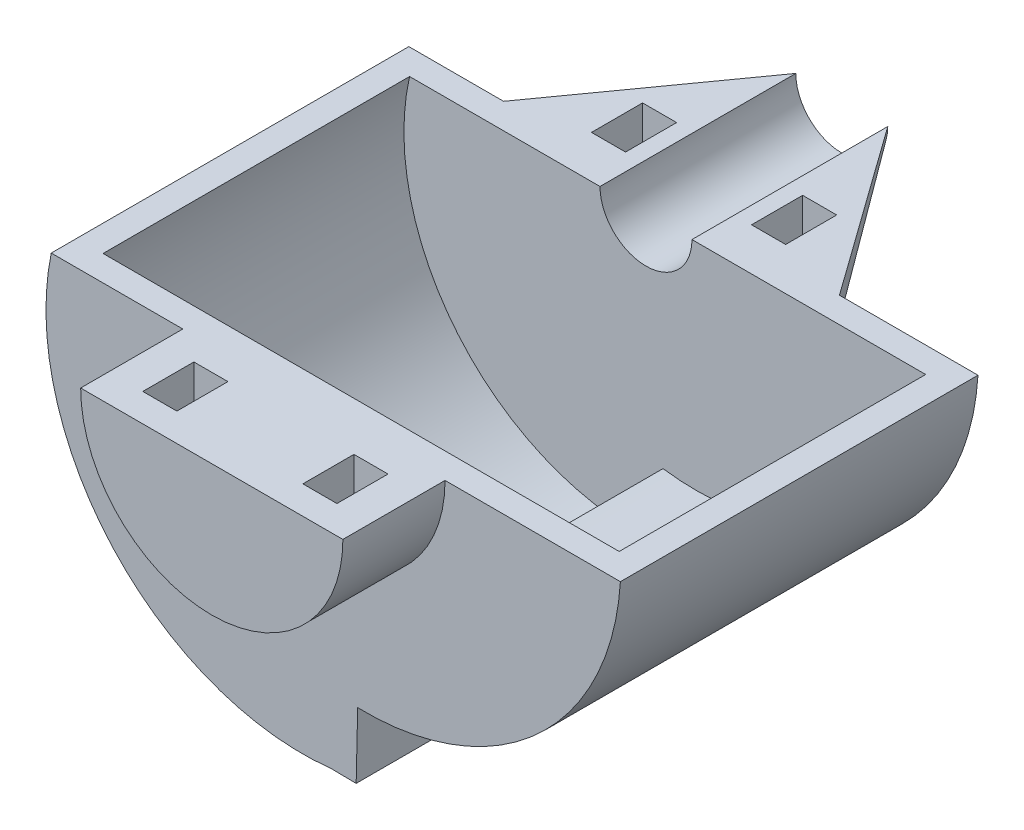
SolidWorks part; units mm, degrees
ref_plane "Alzado" through (0, 0, 0) normal (0, 0, 1) x (1, 0, 0)
ref_plane "Planta" through (0, 0, 0) normal (0, 1, 0) x (1, 0, 0)
ref_plane "Vista lateral" through (0, 0, 0) normal (1, 0, 0) x (0, 0, -1)
sketch "Croquis1" plane through (0, 0, 0) normal (0, 0, 1) x (1, 0, 0)
  line L0 (-54.5351, 31.4828) -> (-55.2579, 32.775)
  line L1 (-69.6242, 5.1176) -> (-68.6242, 5.1176)
  line L2 (-68.6242, 5.1176) -> (-68.6242, 9.1176)
  line L3 (-85.7122, 29.7526) -> (-86.47, 28.4805)
  line L4 (-83.9136, 29.8676) -> (-84.4136, 29.0016)
  line L5 (-84.4136, 29.0016) -> (-80.9495, 27.0016)
  line L6 (-86.47, 28.4805) -> (-83.1384, 26.453)
  line L7 (-55.3348, 29.8676) -> (-55.8348, 30.7337)
  line L8 (-55.8348, 30.7337) -> (-59.2989, 28.7337)
  line L9 (-55.2579, 32.775) -> (-58.6796, 30.9036)
  line L10 (-68.6253, 3.6175) -> (-67.1448, 3.5974)
  line L11 (-67.1448, 3.5974) -> (-67.0547, 7.4963)
  arc A1 (-69.6242, 5.1176) -> (-80.9495, 27.0016) centre (-70.3006, 18.6401) cw
  arc A2 (-55.3348, 29.8676) -> (-68.6242, 9.1176) centre (-66.7074, 22.5206) cw
  arc A3 (-83.9136, 29.8676) -> (-59.2989, 28.7337) centre (-71.8646, 23.6922) cw
  arc A4 (-83.1384, 26.453) -> (-68.6253, 3.6175) centre (-70.3045, 18.58) ccw
  arc A5 (-58.6796, 30.9036) -> (-85.7122, 29.7526) centre (-71.9148, 23.7256) ccw
  arc A6 (-67.0547, 7.4963) -> (-54.5351, 31.4828) centre (-66.6534, 22.5474) ccw
  point P16 (-69.6242, 21.6176)
  point P24 (-69.6242, 21.6176)
  point P33 (-69.6242, 21.6176)
  dimension "D1" = 3
  dimension "D2" = 3
  dimension "D5" = 3
extrude "Saliente-Extruir1" add sketch "Croquis1" along normal blind 18
sketch "Croquis2" plane through (0, 0, 0) normal (0, 0, -1) x (-1, 0, 0)
  line L0 (67.0547, 7.4963) -> (67.1448, 3.5974)
  line L1 (67.1448, 3.5974) -> (68.6253, 3.6175)
  line L2 (58.6796, 30.9036) -> (55.2579, 32.775)
  line L3 (55.2579, 32.775) -> (54.5351, 31.4828)
  line L4 (83.1384, 26.453) -> (86.47, 28.4805)
  line L5 (86.47, 28.4805) -> (85.7122, 29.7526)
  arc A0 (68.6253, 3.6175) -> (83.1384, 26.453) centre (70.3045, 18.58) ccw
  arc A2 (54.5351, 31.4828) -> (67.0547, 7.4963) centre (66.6534, 22.5474) ccw
  arc A3 (85.7122, 29.7526) -> (58.6796, 30.9036) centre (71.9148, 23.7256) ccw
  circle A4 centre (69.6242, 21.6176) radius 2.7
  point P26 (69.6242, 21.6176)
  dimension "D1" = 3
extrude "Saliente-Extruir2" add sketch "Croquis2" along normal blind 1.5
sketch "Croquis3" plane through (0, 0, 18) normal (0, 0, 1) x (1, 0, 0)
  line L0 (-67.1448, 3.5974) -> (-67.0547, 7.4963)
  line L2 (-67.1448, 3.5974) -> (-68.6253, 3.6175)
  line L3 (-86.47, 28.4805) -> (-83.1384, 26.453)
  line L4 (-86.47, 28.4805) -> (-85.7122, 29.7526)
  line L5 (-55.2579, 32.775) -> (-58.6796, 30.9036)
  line L6 (-55.2579, 32.775) -> (-54.5351, 31.4828)
  arc A0 (-68.6253, 3.6175) -> (-83.1384, 26.453) centre (-70.3045, 18.58) cw
  arc A2 (-85.7122, 29.7526) -> (-58.6796, 30.9036) centre (-71.9148, 23.7256) cw
  arc A3 (-54.5351, 31.4828) -> (-67.0547, 7.4963) centre (-66.6534, 22.5474) cw
  dimension "D1" = 3
extrude "Saliente-Extruir3" add sketch "Croquis3" along normal blind 1.5
sketch "Croquis6" plane through (0, 0, -1.5) normal (0, 0, -1) x (-1, 0, 0)
  line L1 (72.3242, 21.6176) -> (66.9242, 21.6176)
  line L2 (72.3242, 21.6176) -> (72.3242, 20.4357)
  line L3 (72.3242, 20.4357) -> (66.9242, 20.4357)
  line L4 (66.9242, 21.6176) -> (66.9242, 20.4357)
  circle A0 centre (69.6242, 21.6176) radius 2.7 construction
extrude "Saliente-Extruir7" add sketch "Croquis6" along normal blind 10
ref_plane "Plano2" through (0, 21.6176, 0) normal (0, 1, 0) x (1, 0, 0)
sketch "Croquis7" plane through (0, 21.6176, 0) normal (0, 1, 0) x (1, 0, 0)
  line L1 (-72.3242, 11.5) -> (-66.9242, 11.5)
  line L2 (-72.3242, 11.5) -> (-72.3242, 1.5)
  line L3 (-72.3242, 1.5) -> (-66.9242, 1.5)
  line L4 (-66.9242, 11.5) -> (-66.9242, 1.5)
extrude "Cortar-Extruir2" cut sketch "Croquis7" against normal up to vertex (16.5 mm away)
sketch "Croquis8" plane through (0, 21.6176, 0) normal (0, 1, 0) x (1, 0, 0)
  line L0 (-72.3242, 1.5) -> (-79.4868, 1.5)
  line L1 (-72.3242, 1.5) -> (-72.3242, 11.5)
  line L2 (-79.4868, 1.5) -> (-72.3242, 11.5)
  line L6 (-72.3242, -19.5) -> (-69.6242, -19.5)
  line L7 (-69.6242, -19.5) -> (-69.6242, -25.5)
  line L8 (-69.6242, -25.5) -> (-72.3242, -25.5)
  line L9 (-77.3242, -25.5) -> (-77.3242, -19.5)
  line L10 (-72.3242, -25.5) -> (-77.3242, -25.5)
  line L11 (-77.3242, -19.5) -> (-72.3242, -19.5)
  dimension "D5" = 21
revolve "Revolución1" add sketch "Croquis8" angle 360 about L7
sketch "Croquis9" plane through (0, 21.6176, 0) normal (0, 1, 0) x (1, 0, 0)
  line L1 (-87.9437, -36.577) -> (-35.4756, -36.577)
  line L2 (-87.9437, -36.577) -> (-87.9437, 19.1063)
  line L3 (-87.9437, 19.1063) -> (-35.4756, 19.1063)
  line L4 (-35.4756, -36.577) -> (-35.4756, 19.1063)
extrude "Cortar-Extruir3" cut sketch "Croquis9" along normal blind 30
sketch "Croquis10" plane through (0, 21.6176, 0) normal (0, 1, 0) x (1, 0, 0)
  line L0 (-72.3242, 0) -> (-72.3242, 11.5) construction
  line L1 (-75.3242, 5.5) -> (-73.3242, 5.5)
  line L2 (-75.3242, 5.5) -> (-75.3242, 2.5)
  line L3 (-75.3242, 2.5) -> (-73.3242, 2.5)
  line L4 (-73.3242, 5.5) -> (-73.3242, 2.5)
  line L5 (-79.4868, 1.5) -> (-85.0513, 1.5) construction
  line L6 (-66.9242, 11.5) -> (-66.9242, 0) construction
  line L7 (-65.9242, 2.5) -> (-63.9232, 2.5)
  line L8 (-65.9242, 2.5) -> (-65.9242, 5.5)
  line L9 (-65.9242, 5.5) -> (-63.9232, 5.5)
  line L10 (-63.9232, 2.5) -> (-63.9232, 5.5)
  line L11 (-51.6257, 1.5) -> (-59.7617, 1.5) construction
  line L13 (-75.3242, -20.85) -> (-73.3242, -20.85)
  line L14 (-75.3242, -20.85) -> (-75.3242, -23.85)
  line L15 (-75.3242, -23.85) -> (-73.3242, -23.85)
  line L16 (-73.3242, -20.85) -> (-73.3242, -23.85)
  line L17 (-65.9242, -20.85) -> (-63.9232, -20.85)
  line L18 (-65.9242, -20.85) -> (-65.9242, -23.85)
  line L19 (-65.9242, -23.85) -> (-63.9232, -23.85)
  line L20 (-63.9232, -20.85) -> (-63.9232, -23.85)
  dimension "D1" = 2
  dimension "D2" = 3
  dimension "D3" = 1
  dimension "D4" = 1
  dimension "D5" = 1
  dimension "D6" = 1
  dimension "D7" = 3
  dimension "D8" = 23.35
  dimension "D9" = 23.35
extrude "Cortar-Extruir4" cut sketch "Croquis10" against normal blind 10
sketch "Croquis11" plane through (-65.9242, 0, 0) normal (1, 0, 0) x (0, 0, -1)
  line L0 (-23.85, 14.8649) -> (-23.85, 21.6176) construction
  line L1 (-23.85, 17.552) -> (-20.8462, 17.552)
  line L2 (-23.85, 17.552) -> (-23.85, 9.1747)
  line L3 (-23.85, 9.1747) -> (-20.8462, 9.1747)
  line L4 (-20.8462, 17.552) -> (-20.8462, 9.1747)
  line L5 (2.5, 13.2531) -> (2.5, 21.6176) construction
  line L6 (2.5, 16.264) -> (5.5, 16.264)
  line L7 (2.5, 16.264) -> (2.5, 9.6833)
  line L8 (2.5, 9.6833) -> (5.5, 9.6833)
  line L9 (5.5, 16.264) -> (5.5, 9.6833)
extrude "Cortar-Extruir5" cut sketch "Croquis11" against normal up to vertex (7.4 mm away)
